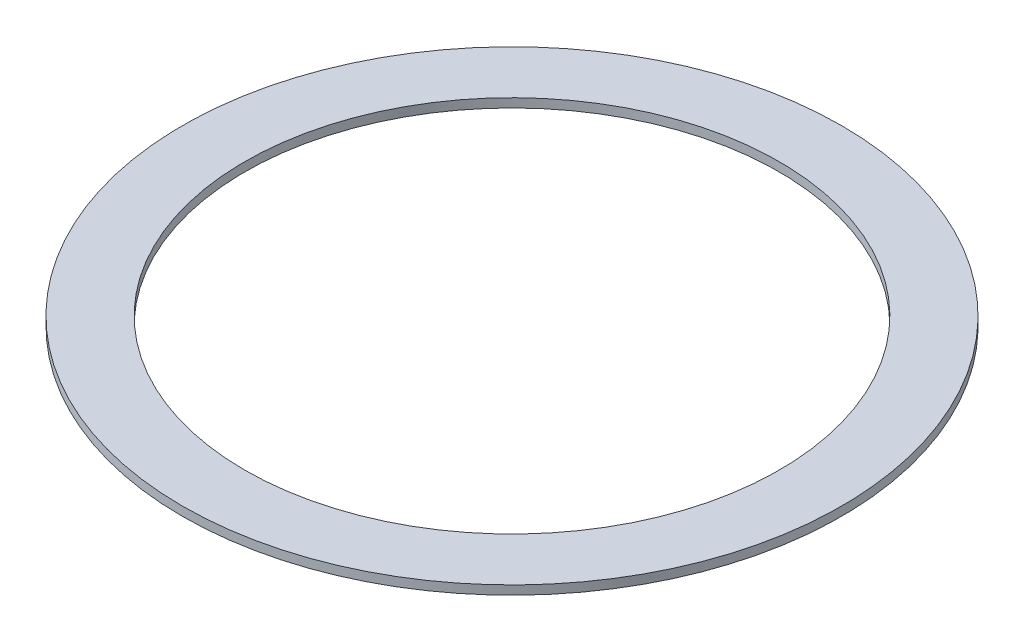
SolidWorks part; units mm, degrees
ref_plane "Front Plane" through (0, 0, 0) normal (0, 0, 1) x (1, 0, 0)
ref_plane "Top Plane" through (0, 0, 0) normal (0, 1, 0) x (1, 0, 0)
ref_plane "Right Plane" through (0, 0, 0) normal (1, 0, 0) x (0, 0, -1)
sketch "Sketch1" plane through (0, 0, 0) normal (0, 1, 0) x (1, 0, 0)
  circle A0 centre (0, 0) radius 60
  circle A1 centre (0, 0) radius 74
  dimension "D1" = 148
  dimension "D2" = 120
extrude "Boss-Extrude1" add sketch "Sketch1" along normal blind 2
